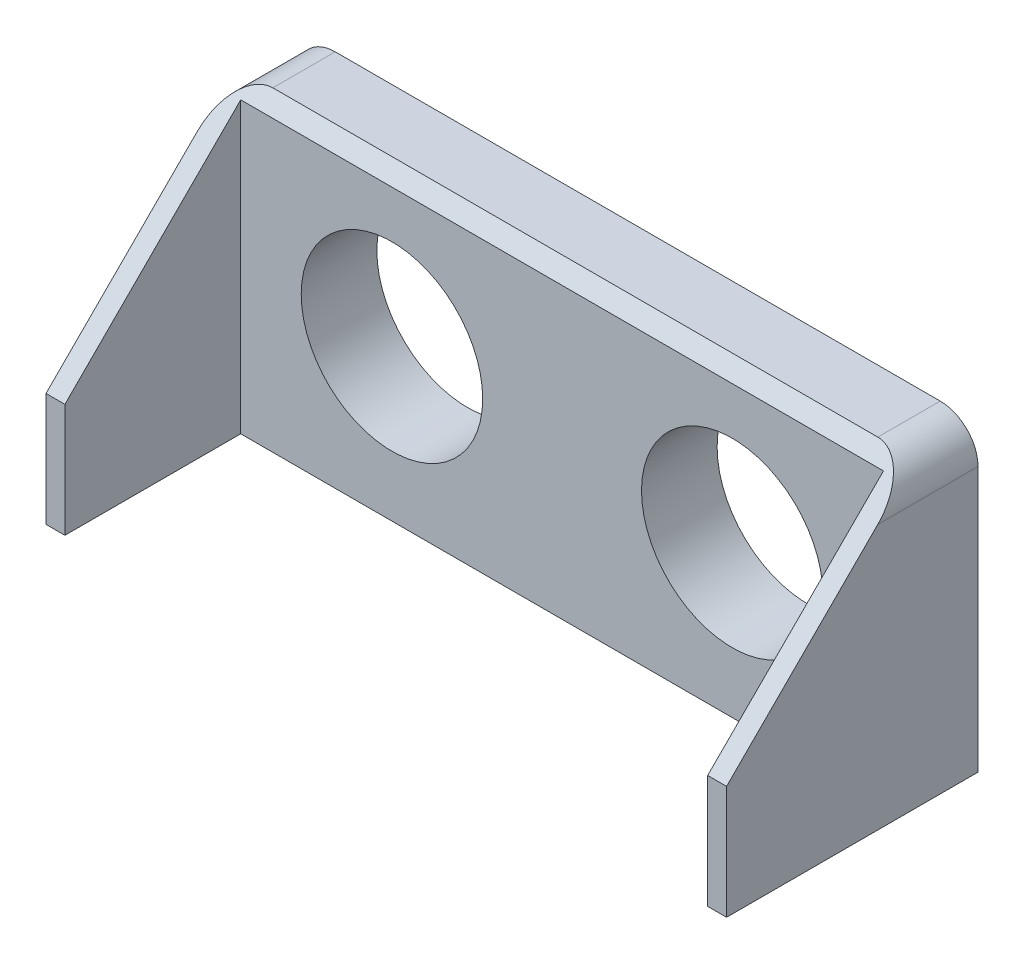
SolidWorks part; units mm, degrees
ref_plane "Front Plane" through (0, 0, 0) normal (0, 0, 1) x (1, 0, 0)
ref_plane "Top Plane" through (0, 0, 0) normal (0, 1, 0) x (1, 0, 0)
ref_plane "Right Plane" through (0, 0, 0) normal (1, 0, 0) x (0, 0, -1)
sketch "Sketch2" plane through (0, 0, 0) normal (0, 1, 0) x (1, 0, 0)
  line L0 (0, 0) -> (0, 13.3)
  line L1 (0, 13.3) -> (36, 13.3)
  line L2 (36, 13.3) -> (36, 0)
  line L3 (36, 0) -> (35, 0)
  line L4 (35, 0) -> (35, 9.3)
  line L5 (35, 9.3) -> (1, 9.3)
  line L6 (1, 9.3) -> (1, 0)
  line L7 (1, 0) -> (0, 0)
  dimension "D1" = 36
  dimension "D2" = 13.3
  dimension "D3" = 1
  dimension "D4" = 1
  dimension "D5" = 4
extrude "Boss-Extrude1" add sketch "Sketch2" along normal blind 16
chamfer "Chamfer1" distance 10 angle 45 1 edges at (0.5, 16, 0)
fillet "Fillet1" radius 2 2 edges at (36, 16, -11.65) (0, 16, -11.65)
sketch "Sketch3" plane through (0, 0, -13.3) normal (0, 0, -1) x (-1, 0, 0)
  line L0 (-18, 16) -> (-18, 0) construction
  line L1 (-34, 16) -> (-2, 16) construction
  line L2 (-36, 0) -> (0, 0) construction
  line L3 (-18, 8) -> (0, 8) construction
  line L4 (0, 14) -> (0, 0) construction
  line L5 (-18, 8) -> (-36, 8) construction
  line L6 (-36, 14) -> (-36, 0) construction
  circle A0 centre (-27, 8) radius 4.8
  circle A1 centre (-9, 8) radius 4.8
  dimension "D1" = 9.6
  dimension "D2" = 9
extrude "Cut-Extrude1" cut sketch "Sketch3" against normal through all
